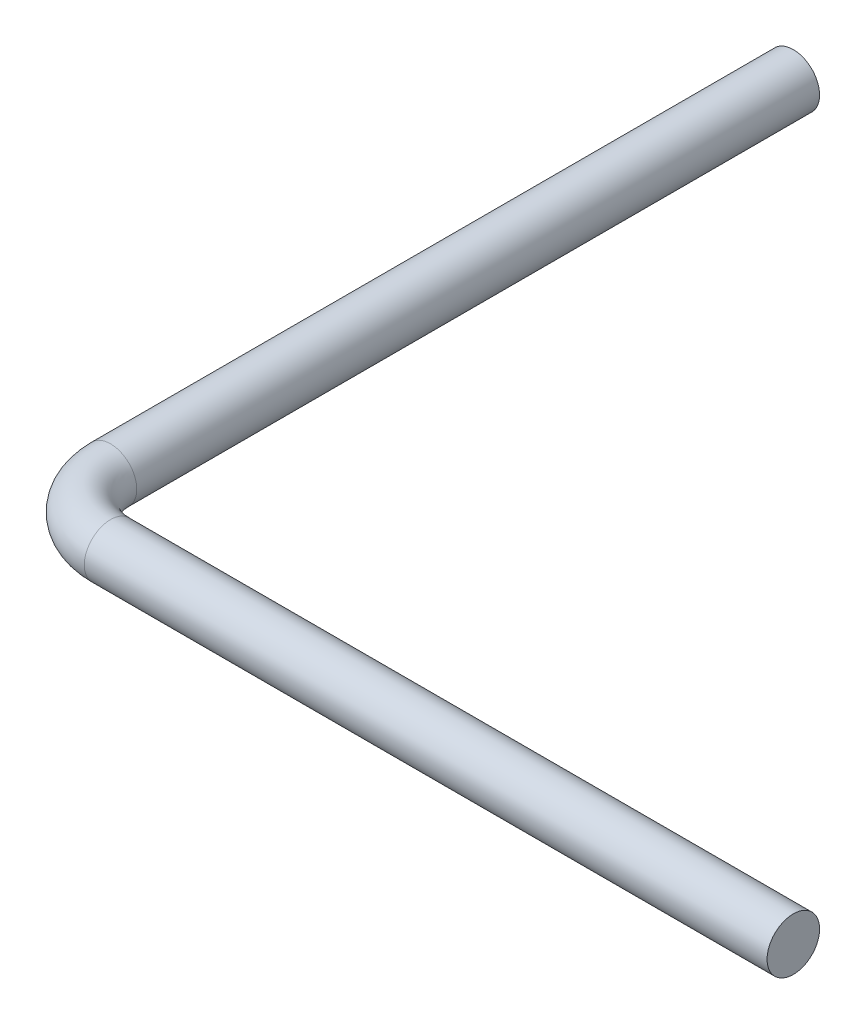
SolidWorks part; units mm, degrees
ref_plane "正面" through (0, 0, 0) normal (0, 0, 1) x (1, 0, 0)
ref_plane "平面" through (0, 0, 0) normal (0, 1, 0) x (1, 0, 0)
ref_plane "右側面" through (0, 0, 0) normal (1, 0, 0) x (0, 0, -1)
sketch "ｽｹｯﾁ1" plane through (0, 0, 0) normal (0, 0, 1) x (1, 0, 0)
  circle A0 centre (0, 0) radius 2
  dimension "D1" = 4
extrude "ﾎﾞｽ - 押し出し1" add sketch "ｽｹｯﾁ1" along normal blind 50
sketch "ｽｹｯﾁ2" plane through (0, 0, 0) normal (0, 1, 0) x (1, 0, 0)
  line L0 (0, -50) -> (0, -52)
  line L1 (-2, -50) -> (2, -50) construction
  line L2 (5, -57) -> (57, -57)
  arc A0 (0, -52) -> (5, -57) centre (5, -52) ccw
  point P5 (-22.0519, -39.8677)
  dimension "D1" = 5
  dimension "D2" = 2
  dimension "D3" = 52
sketch "ｽｹｯﾁ3" plane through (0, 0, 50) normal (0, 0, 1) x (1, 0, 0)
  circle A1 centre (0, 0) radius 2
  circle A2 centre (0, 0) radius 2
  dimension "D1" = 0
sweep "ｽｲｰﾌﾟ1" add profiles "ｽｹｯﾁ3" path "ｽｹｯﾁ2"
